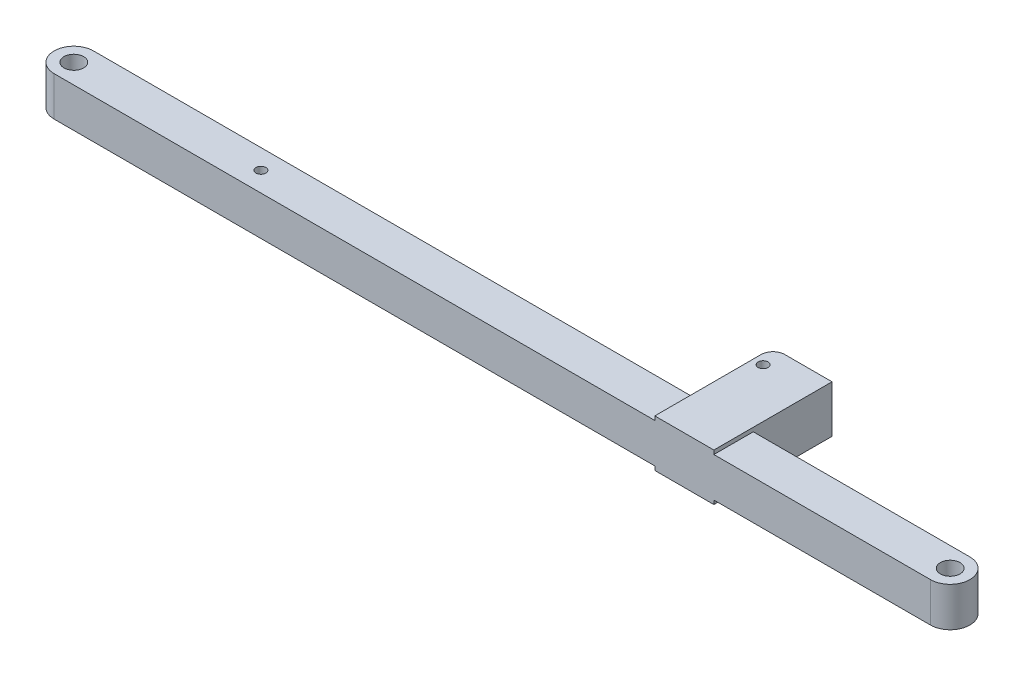
SolidWorks part; units mm, degrees
ref_plane "Front Plane" through (0, 0, 0) normal (0, 0, 1) x (1, 0, 0)
ref_plane "Top Plane" through (0, 0, 0) normal (0, 1, 0) x (1, 0, 0)
ref_plane "Right Plane" through (0, 0, 0) normal (1, 0, 0) x (0, 0, -1)
sketch "Sketch2" plane through (0, 0, 0) normal (0, 1, 0) x (1, 0, 0)
  line L0 (0, 0) -> (120.65, 0)
  line L1 (0, 0) -> (565.15, 0)
  line L2 (0, 0) -> (0, 25.4) construction
  line L3 (0, 25.4) -> (565.15, 25.4)
  line L4 (565.15, 0) -> (565.15, 25.4) construction
  line L5 (120.65, 0) -> (120.65, 25.4) construction
  circle A0 centre (120.65, 12.7) radius 12.7
  arc A1 (565.15, 25.4) -> (565.15, 0) centre (565.15, 12.7) cw
  circle A2 centre (120.65, 12.7) radius 3.175
  circle A3 centre (565.15, 12.7) radius 6.35
  arc A4 (0, 25.4) -> (0, 0) centre (0, 12.7) ccw
  circle A5 centre (0, 12.7) radius 6.35
  dimension "D4" = 6.35
  dimension "D5" = 12.7
  dimension "D6" = 12.7
  dimension "D1" = 565.15
  dimension "D2" = 25.4
  dimension "D3" = 120.65
extrude "Boss-Extrude1" add sketch "Sketch2" along normal blind 25.4 contours A0 L3 L2 L0 | A0 A2 | A1 L3 A0 L1 A3
sketch "Sketch12" plane through (0, 0, -25.4) normal (0, 0, -1) x (-1, 0, 0)
  line L0 (-565.15, 25.4) -> (-425.45, 25.4)
  line L1 (0, 25.4) -> (-565.15, 25.4) construction
  line L2 (-387.35, 27.94) -> (-425.45, 27.94)
  line L3 (-425.45, 27.94) -> (-425.45, -2.54)
  line L4 (-425.45, -2.54) -> (-387.35, -2.54)
  line L5 (-387.35, -2.54) -> (-387.35, 27.94)
  line M1 (-565.15, 0) -> (0, 0)
  line M3 (0, 25.4) -> (-565.15, 25.4)
  dimension "D1" = 139.7
  dimension "D2" = 38.1
  dimension "D3" = 2.54
  dimension "D4" = 30.48
extrude "Boss-Extrude2" add sketch "Sketch12" against normal blind 25.4 contours L5 L3 M1 M3 | L4 L5 L3 M1 | L5 L2 L3 M3
sketch "Sketch13" plane through (0, 0, -25.4) normal (0, 0, -1) x (-1, 0, 0)
  line L0 (-425.45, 27.94) -> (-425.45, -2.54)
  line L1 (-425.45, -2.54) -> (-387.35, -2.54)
  line L2 (-425.45, -2.54) -> (-387.35, -2.54) construction
  line L3 (-387.35, -2.54) -> (-387.35, 27.94)
  line L4 (-387.35, 27.94) -> (-425.45, 27.94)
  line L5 (-419.1, 21.59) -> (-419.1, 3.81)
  line L6 (-419.1, 3.81) -> (-387.35, 3.81)
  line L7 (-419.1, 21.59) -> (-387.35, 21.59)
  line M2 (-387.35, 25.4) -> (-387.35, 27.94)
  line M3 (-387.35, 27.94) -> (-425.45, 27.94)
  line M4 (-425.45, 27.94) -> (-425.45, 25.4)
  line M8 (-425.45, 0) -> (-425.45, -2.54)
  line M9 (-425.45, -2.54) -> (-387.35, -2.54)
  line M10 (-387.35, -2.54) -> (-387.35, 0)
  dimension "D1" = 6.35
  dimension "D2" = 6.35
  dimension "D3" = 6.35
extrude "Boss-Extrude3" add sketch "Sketch13" along normal blind 50.8 contours L5 L7 L3 L0 L6 M2 M3 M4 M8 M9 M10
sketch "Sketch14" plane through (0, 21.59, 0) normal (0, -1, 0) x (1, 0, 0)
  line L0 (387.35, -63.5) -> (393.7, -63.5) construction
  line L2 (387.35, -76.2) -> (387.35, -25.4) construction
  circle A0 centre (393.7, -63.5) radius 3.175
  dimension "D2" = 6.35
  dimension "D1" = 6.35
  dimension "D3" = 12.7
extrude "Cut-Extrude1" cut sketch "Sketch14" along normal mid plane 79.248
fillet "Fillet1" radius 7.62 2 edges at (387.35, 0.635, -76.2) (387.35, 24.765, -76.2)
